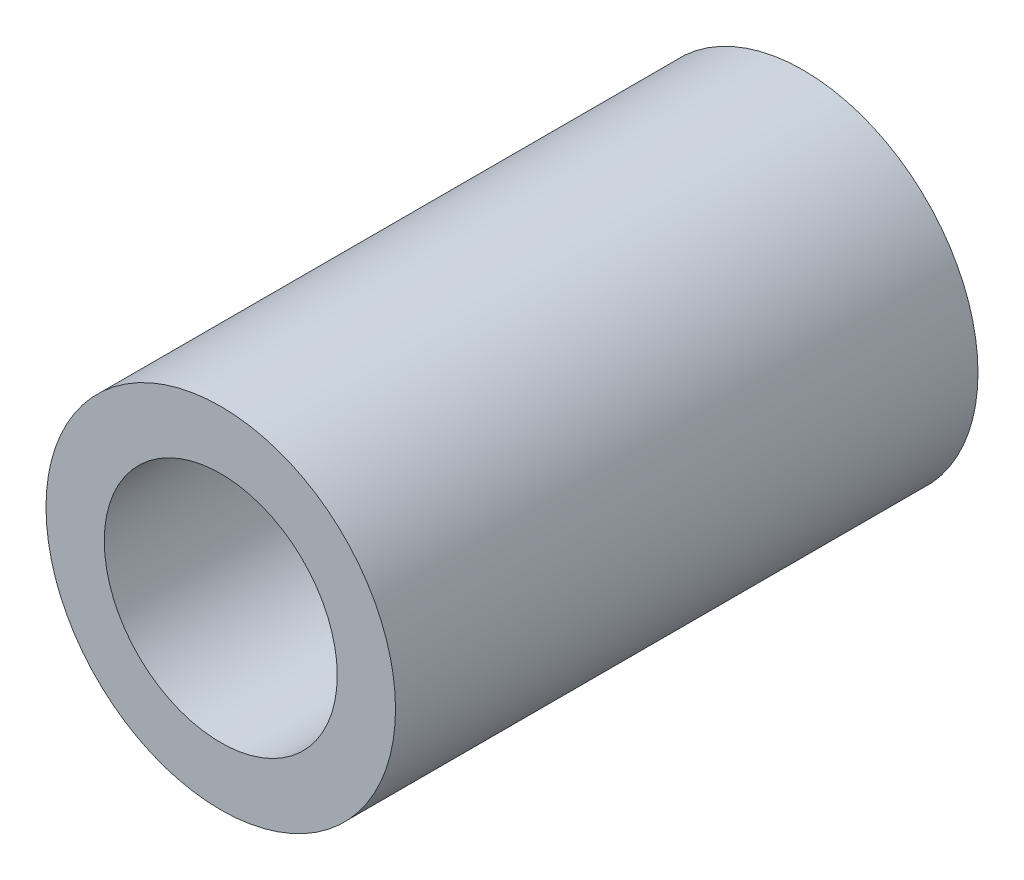
SolidWorks part; units mm, degrees
ref_plane "Front Plane" through (0, 0, 0) normal (0, 0, 1) x (1, 0, 0)
ref_plane "Top Plane" through (0, 0, 0) normal (0, 1, 0) x (1, 0, 0)
ref_plane "Right Plane" through (0, 0, 0) normal (1, 0, 0) x (0, 0, -1)
sketch "Sketch1" plane through (0, 0, 0) normal (0, 0, 1) x (1, 0, 0)
  circle A0 centre (0, 0) radius 50.8
  circle A1 centre (0, 0) radius 76.2
  dimension "D1" = 101.6
  dimension "D2" = 152.4
extrude "Boss-Extrude1" add sketch "Sketch1" along normal mid plane 254
